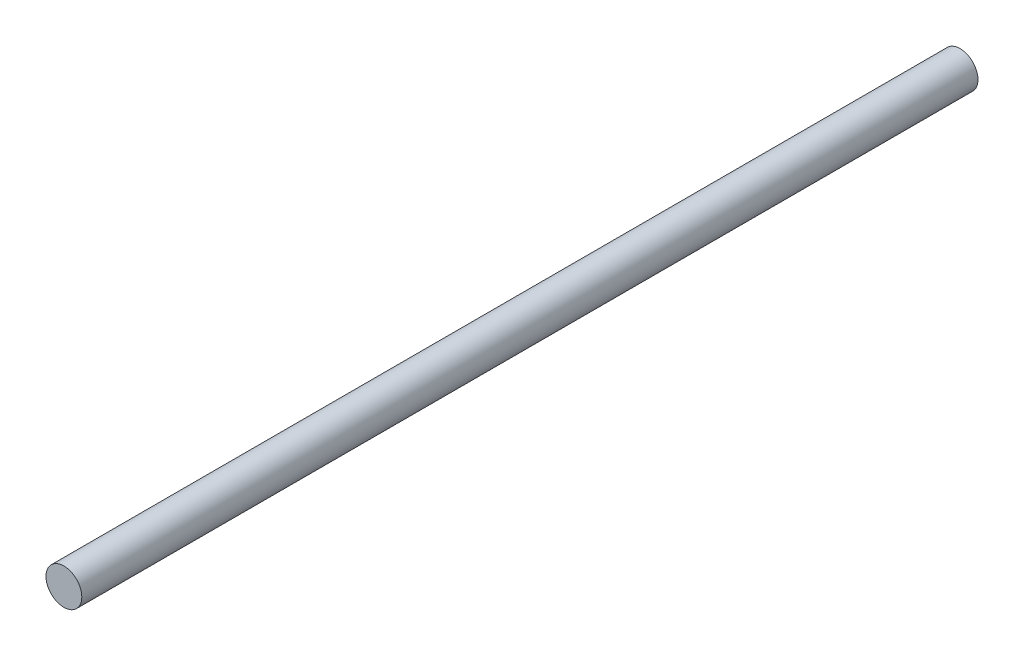
SolidWorks part; units mm, degrees
ref_plane "Płaszczyzna przednia" through (0, 0, 0) normal (0, 0, 1) x (1, 0, 0)
ref_plane "Płaszczyzna górna" through (0, 0, 0) normal (0, 1, 0) x (1, 0, 0)
ref_plane "Płaszczyzna prawa" through (0, 0, 0) normal (1, 0, 0) x (0, 0, -1)
sketch "Szkic1" plane through (0, 0, 0) normal (0, 0, 1) x (1, 0, 0)
  circle A0 centre (0, 0) radius 4
  dimension "D1" = 8
extrude "Dodanie-wyciągnięcie1" add sketch "Szkic1" along normal blind 200
